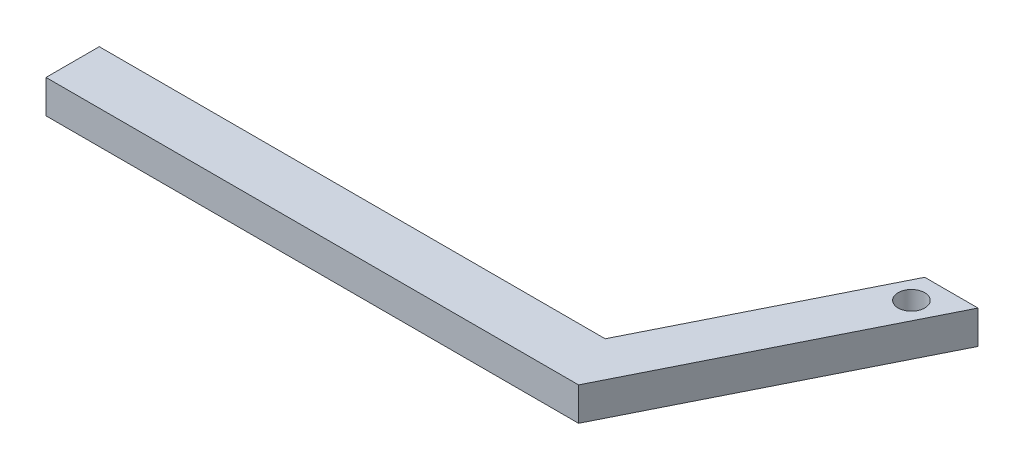
SolidWorks part; units mm, degrees
ref_plane "Front Plane" through (0, 0, 0) normal (0, 0, 1) x (1, 0, 0)
ref_plane "Top Plane" through (0, 0, 0) normal (0, 1, 0) x (1, 0, 0)
ref_plane "Right Plane" through (0, 0, 0) normal (1, 0, 0) x (0, 0, -1)
sketch "Sketch1" plane through (0, 0, 0) normal (0, 0, 1) x (1, 0, 0)
  line L0 (-25.4, -1.5875) -> (25.4, -1.5875)
  line L1 (-25.4, -1.5875) -> (-25.4, 1.5875)
  line L2 (25.4, -1.5875) -> (25.4, 1.5875)
  line L3 (-25.4, 1.5875) -> (25.4, 1.5875)
  line L4 (-25.4, -1.5875) -> (25.4, 1.5875) construction
  line L5 (25.4, -1.5875) -> (-25.4, 1.5875) construction
  point P1 (0, 0)
  dimension "D1" = 50.8
  dimension "D2" = 3.175
extrude "Boss-Extrude1" add sketch "Sketch1" along normal blind 5.08
sketch "Sketch2" plane through (0, -1.5875, 0) normal (0, -1, 0) x (-1, 0, 0)
  line L0 (-25.4, -5.08) -> (-38.1, 20.32)
  line L1 (-38.1, 20.32) -> (-33.02, 20.32)
  line L2 (-33.02, 20.32) -> (-20.32, -5.08)
  line L3 (25.4, -5.08) -> (-25.4, -5.08) construction
  line L4 (-20.32, -5.08) -> (-25.4, -5.08)
  line L5 (-36.83, 17.78) -> (-31.75, 17.78) construction
  circle A0 centre (-34.29, 17.78) radius 1.27
  point P12 (-34.29, 17.78)
  point P13 (-34.29, 19.05)
  dimension "D1" = 2.54
  dimension "D2" = 5.08
  dimension "D3" = 1.27
  dimension "D4" = 25.4
  dimension "D5" = 12.7
extrude "Boss-Extrude2" add sketch "Sketch2" against normal up to surface (3.175 mm away) up to face at (0, 1.5875, 2.54)
